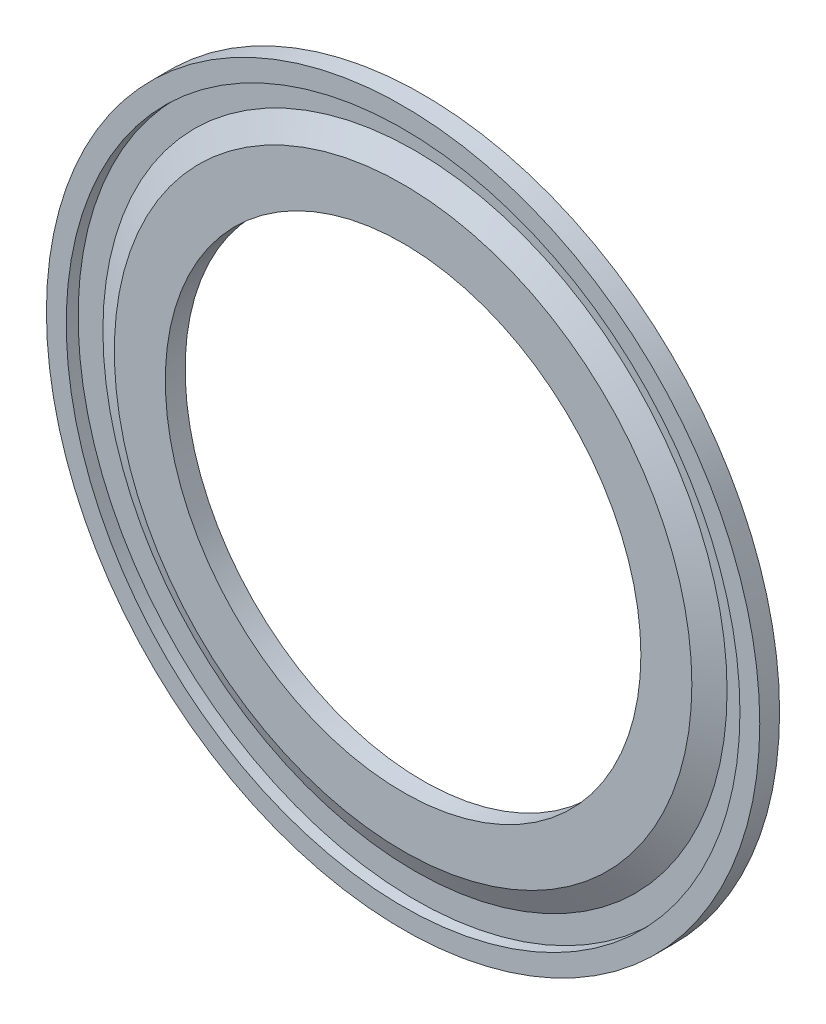
SolidWorks part; units mm, degrees
material "Caoutchouc silicone"
ref_plane "Plan de face" through (0, 0, 0) normal (0, 0, 1) x (1, 0, 0)
ref_plane "Plan de dessus" through (0, 0, 0) normal (0, 1, 0) x (1, 0, 0)
ref_plane "Plan de droite" through (0, 0, 0) normal (1, 0, 0) x (0, 0, -1)
sketch "Esquisse1" plane through (0, 0, 0) normal (1, 0, 0) x (0, 0, -1)
  line L0 (0, 0) -> (0, 4.3836) construction
  line L1 (-0.5, 17) -> (0.1, 17)
  line L2 (-0.5, 12) -> (0.5, 12)
  line L3 (-0.5, 12) -> (-0.5, 14.5724)
  line L4 (-0.5, 18) -> (0.5, 18)
  line L5 (0, 0) -> (2.9793, 0) construction
  line L6 (0.5, 12) -> (0.5, 18)
  line L7 (0.1, 17) -> (0.1, 15.75)
  line L8 (0.1, 15.75) -> (-0.5, 14.5724)
  line L9 (-0.5, 17) -> (-0.5, 18)
  dimension "D1" = 1
  dimension "D2" = 12
  dimension "D3" = 18
  dimension "D4" = 1
  dimension "D5" = 0.6
  dimension "D6" = 1.25
  dimension "D7" = 27
revolve "Révolution1" add sketch "Esquisse1" angle 360 about L5
